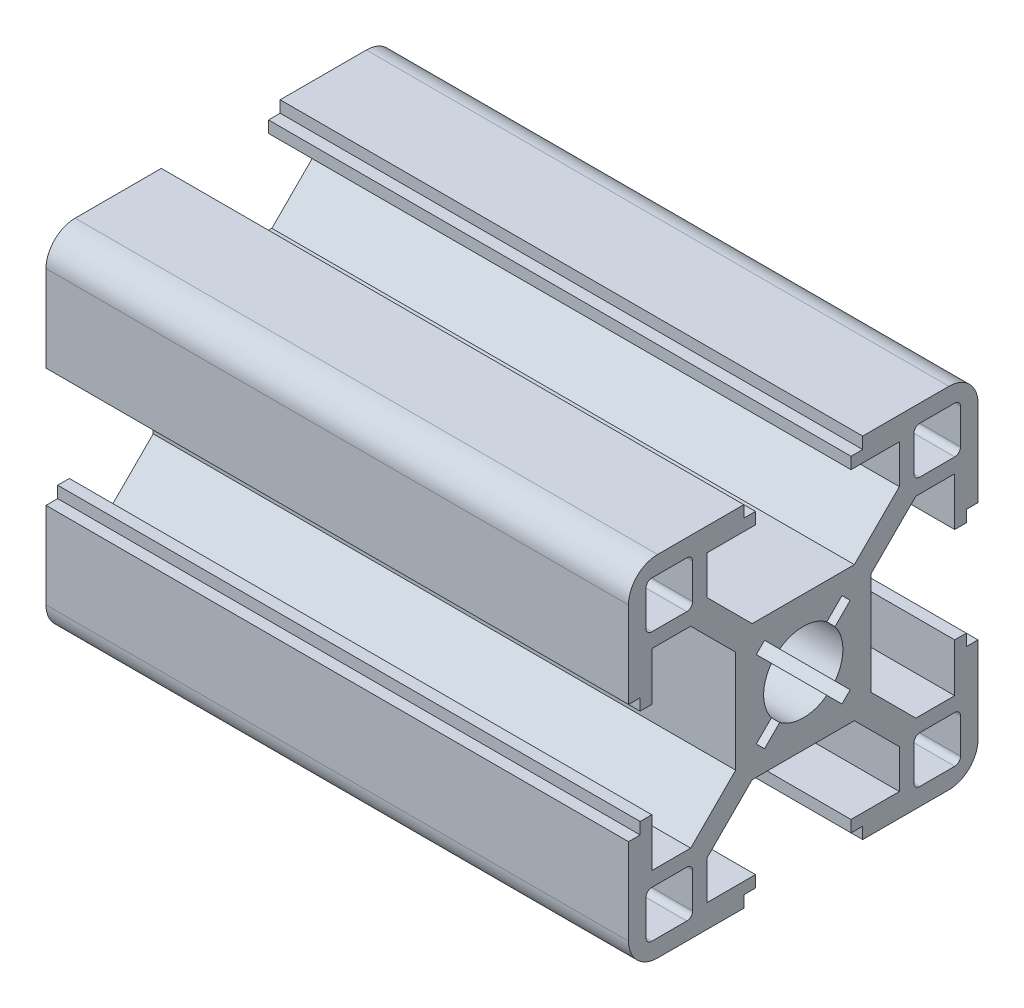
SolidWorks part; units mm, degrees
ref_plane "前视基准面" through (0, 0, 0) normal (0, 0, 1) x (1, 0, 0)
ref_plane "上视基准面" through (0, 0, 0) normal (0, 1, 0) x (1, 0, 0)
ref_plane "右视基准面" through (0, 0, 0) normal (1, 0, 0) x (0, 0, -1)
other "Configuration Table"
sketch "草图1" plane through (0, 0, 0) normal (1, 0, 0) x (0, 0, -1)
  line L0 (-5.1496, -13.7047) -> (-4.1496, -13.7047)
  line L1 (-4.1496, -13.7047) -> (-4.1496, -12.7047)
  line L2 (-4.1496, -12.7047) -> (-8.2996, -12.7047)
  line L3 (-8.2996, -12.7047) -> (-8.2996, -9.3689)
  line L4 (-8.2996, -9.3689) -> (-4.4354, -5.5047)
  line L5 (-4.4354, -5.5047) -> (4.3362, -5.5047)
  line L6 (4.3362, -5.5047) -> (8.2004, -9.3689)
  line L7 (8.2004, -9.3689) -> (8.2004, -12.7047)
  line L8 (8.2004, -12.7047) -> (4.0504, -12.7047)
  line L9 (4.0504, -12.7047) -> (4.0504, -13.7047)
  line L10 (4.0504, -13.7047) -> (5.0504, -13.7047)
  line L11 (5.0504, -13.7047) -> (5.0504, -14.7047)
  line L12 (5.0504, -14.7047) -> (12.4504, -14.7047)
  line L13 (14.9504, -12.2047) -> (14.9504, -4.8047)
  line L14 (14.9504, -4.8047) -> (13.9504, -4.8047)
  line L15 (13.9504, -4.8047) -> (13.9504, -3.8047)
  line L16 (13.9504, -3.8047) -> (12.9504, -3.8047)
  line L17 (12.9504, -3.8047) -> (12.9504, -7.9547)
  line L18 (12.9504, -7.9547) -> (9.6146, -7.9547)
  line L19 (9.6146, -7.9547) -> (5.7504, -4.0905)
  line L20 (5.7504, -4.0905) -> (5.7504, 4.6811)
  line L21 (5.7504, 4.6811) -> (9.6146, 8.5453)
  line L22 (9.6146, 8.5453) -> (12.9504, 8.5453)
  line L23 (12.9504, 8.5453) -> (12.9504, 4.3953)
  line L24 (12.9504, 4.3953) -> (13.9504, 4.3953)
  line L25 (13.9504, 4.3953) -> (13.9504, 5.3953)
  line L26 (13.9504, 5.3953) -> (14.9504, 5.3953)
  line L27 (14.9504, 5.3953) -> (14.9504, 12.7953)
  line L28 (12.4504, 15.2953) -> (5.0504, 15.2953)
  line L29 (5.0504, 15.2953) -> (5.0504, 14.2953)
  line L30 (5.0504, 14.2953) -> (4.0504, 14.2953)
  line L31 (4.0504, 14.2953) -> (4.0504, 13.2953)
  line L32 (4.0504, 13.2953) -> (8.2004, 13.2953)
  line L33 (8.2004, 13.2953) -> (8.2004, 9.9595)
  line L34 (8.2004, 9.9595) -> (4.3362, 6.0953)
  line L35 (4.3362, 6.0953) -> (-4.4354, 6.0953)
  line L36 (-4.4354, 6.0953) -> (-8.2996, 9.9595)
  line L37 (-8.2996, 9.9595) -> (-8.2996, 13.2953)
  line L38 (-8.2996, 13.2953) -> (-4.1496, 13.2953)
  line L39 (-4.1496, 13.2953) -> (-4.1496, 14.2953)
  line L40 (-4.1496, 14.2953) -> (-5.1496, 14.2953)
  line L41 (-5.1496, 14.2953) -> (-5.1496, 15.2953)
  line L42 (-5.1496, 15.2953) -> (-12.5496, 15.2953)
  line L43 (-15.0496, 12.7953) -> (-15.0496, 5.3953)
  line L44 (-15.0496, 5.3953) -> (-14.0496, 5.3953)
  line L45 (-14.0496, 5.3953) -> (-14.0496, 4.3953)
  line L46 (-14.0496, 4.3953) -> (-13.0496, 4.3953)
  line L47 (-13.0496, 4.3953) -> (-13.0496, 8.5453)
  line L48 (-13.0496, 8.5453) -> (-9.7138, 8.5453)
  line L49 (-9.7138, 8.5453) -> (-5.8496, 4.6811)
  line L50 (-5.8496, 4.6811) -> (-5.8496, -4.0905)
  line L51 (-5.8496, -4.0905) -> (-9.7138, -7.9547)
  line L52 (-9.7138, -7.9547) -> (-13.0496, -7.9547)
  line L53 (-13.0496, -7.9547) -> (-13.0496, -3.8047)
  line L54 (-13.0496, -3.8047) -> (-14.0496, -3.8047)
  line L55 (-14.0496, -3.8047) -> (-14.0496, -4.8047)
  line L56 (-14.0496, -4.8047) -> (-15.0496, -4.8047)
  line L57 (-15.0496, -4.8047) -> (-15.0496, -12.2047)
  line L58 (-12.5496, -14.7047) -> (-5.1496, -14.7047)
  line L59 (-5.1496, -14.7047) -> (-5.1496, -13.7047)
  line L60 (-10.0496, 9.7953) -> (-13.0496, 9.7953)
  line L61 (-13.5496, 10.2953) -> (-13.5496, 13.2953)
  line L62 (-13.0496, 13.7953) -> (-10.0496, 13.7953)
  line L63 (-9.5496, 13.2953) -> (-9.5496, 10.2953)
  line L64 (-10.0496, -13.2047) -> (-13.0496, -13.2047)
  line L65 (-13.5496, -12.7047) -> (-13.5496, -9.7047)
  line L66 (-13.0496, -9.2047) -> (-10.0496, -9.2047)
  line L67 (-9.5496, -9.7047) -> (-9.5496, -12.7047)
  line L68 (12.9504, 9.7953) -> (9.9504, 9.7953)
  line L69 (9.4504, 10.2953) -> (9.4504, 13.2953)
  line L70 (9.9504, 13.7953) -> (12.9504, 13.7953)
  line L71 (13.4504, 13.2953) -> (13.4504, 10.2953)
  line L72 (13.4504, -9.7047) -> (13.4504, -12.7047)
  line L73 (12.9504, -13.2047) -> (9.9504, -13.2047)
  line L74 (9.4504, -12.7047) -> (9.4504, -9.7047)
  line L75 (9.9504, -9.2047) -> (12.9504, -9.2047)
  line L76 (-4.08, 3.6186) -> (-3.3729, 4.3257)
  line L77 (-3.3729, 4.3257) -> (-2.074, 3.0269)
  line L78 (1.9749, 3.0269) -> (3.2737, 4.3257)
  line L79 (3.2737, 4.3257) -> (3.9808, 3.6186)
  line L80 (3.9808, 3.6186) -> (2.682, 2.3198)
  line L81 (2.682, -1.7291) -> (3.9808, -3.028)
  line L82 (3.9808, -3.028) -> (3.2737, -3.7351)
  line L83 (3.2737, -3.7351) -> (1.9749, -2.4362)
  line L84 (-2.074, -2.4362) -> (-3.3729, -3.7351)
  line L85 (-3.3729, -3.7351) -> (-4.08, -3.028)
  line L86 (-4.08, -3.028) -> (-2.7811, -1.7291)
  line L87 (-2.7811, 2.3198) -> (-4.08, 3.6186)
  arc A0 (12.4504, -14.7047) -> (14.9504, -12.2047) centre (12.4504, -12.2047) ccw
  arc A1 (14.9504, 12.7953) -> (12.4504, 15.2953) centre (12.4504, 12.7953) ccw
  arc A2 (-12.5496, 15.2953) -> (-15.0496, 12.7953) centre (-12.5496, 12.7953) ccw
  arc A3 (-15.0496, -12.2047) -> (-12.5496, -14.7047) centre (-12.5496, -12.2047) ccw
  arc A4 (-9.5496, 10.2953) -> (-10.0496, 9.7953) centre (-10.0496, 10.2953) cw
  arc A5 (-13.0496, 9.7953) -> (-13.5496, 10.2953) centre (-13.0496, 10.2953) cw
  arc A6 (-13.5496, 13.2953) -> (-13.0496, 13.7953) centre (-13.0496, 13.2953) cw
  arc A7 (-10.0496, 13.7953) -> (-9.5496, 13.2953) centre (-10.0496, 13.2953) cw
  arc A8 (-9.5496, -12.7047) -> (-10.0496, -13.2047) centre (-10.0496, -12.7047) cw
  arc A9 (-13.0496, -13.2047) -> (-13.5496, -12.7047) centre (-13.0496, -12.7047) cw
  arc A10 (-13.5496, -9.7047) -> (-13.0496, -9.2047) centre (-13.0496, -9.7047) cw
  arc A11 (-10.0496, -9.2047) -> (-9.5496, -9.7047) centre (-10.0496, -9.7047) cw
  arc A12 (13.4504, 10.2953) -> (12.9504, 9.7953) centre (12.9504, 10.2953) cw
  arc A13 (9.9504, 9.7953) -> (9.4504, 10.2953) centre (9.9504, 10.2953) cw
  arc A14 (9.4504, 13.2953) -> (9.9504, 13.7953) centre (9.9504, 13.2953) cw
  arc A15 (12.9504, 13.7953) -> (13.4504, 13.2953) centre (12.9504, 13.2953) cw
  arc A16 (12.9504, -9.2047) -> (13.4504, -9.7047) centre (12.9504, -9.7047) cw
  arc A17 (13.4504, -12.7047) -> (12.9504, -13.2047) centre (12.9504, -12.7047) cw
  arc A18 (9.9504, -13.2047) -> (9.4504, -12.7047) centre (9.9504, -12.7047) cw
  arc A19 (9.4504, -9.7047) -> (9.9504, -9.2047) centre (9.9504, -9.7047) cw
  arc A20 (-2.074, 3.0269) -> (1.9749, 3.0269) centre (-0.0496, 0.2953) cw
  arc A21 (2.682, 2.3198) -> (2.682, -1.7291) centre (-0.0496, 0.2953) cw
  arc A22 (1.9749, -2.4362) -> (-2.074, -2.4362) centre (-0.0496, 0.2953) cw
  arc A23 (-2.7811, -1.7291) -> (-2.7811, 2.3198) centre (-0.0496, 0.2953) cw
extrude "凸台-拉伸1" add sketch "草图1" against normal blind 50
